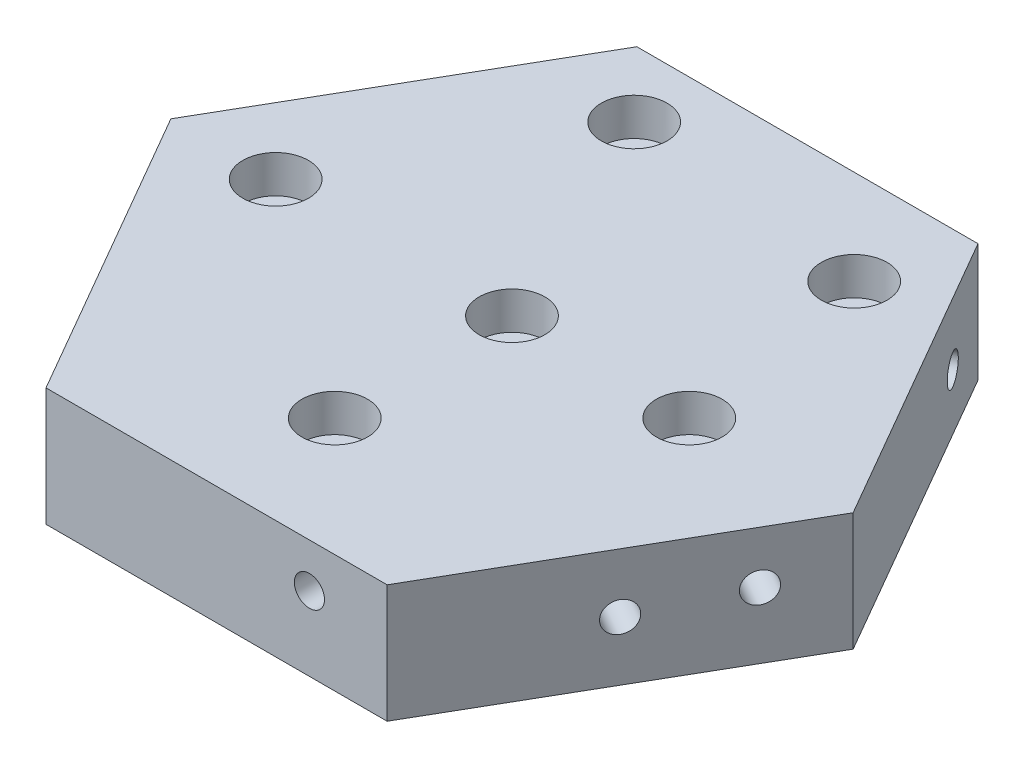
SolidWorks part; units mm, degrees
material "AISI 1020"
ref_plane "Front Plane" through (0, 0, 0) normal (0, 0, 1) x (1, 0, 0)
ref_plane "Top Plane" through (0, 0, 0) normal (0, 1, 0) x (1, 0, 0)
ref_plane "Right Plane" through (0, 0, 0) normal (1, 0, 0) x (0, 0, -1)
sketch "Sketch1" plane through (0, 0, 0) normal (0, 1, 0) x (1, 0, 0)
  line L0 (-43.3013, 25) -> (43.3013, -25) construction
  line L1 (28.8675, 50) -> (-28.8675, 50)
  line L2 (-28.8675, 50) -> (-57.735, 0)
  line L3 (-57.735, 0) -> (-28.8675, -50)
  line L4 (-28.8675, -50) -> (28.8675, -50)
  line L5 (28.8675, -50) -> (57.735, 0)
  line L6 (57.735, 0) -> (28.8675, 50)
  line L7 (0, -50) -> (0, 50) construction
  line L8 (-43.3013, -25) -> (43.3013, 25) construction
  circle A0 centre (0, 0) radius 50 construction
  dimension "D1" = 100
extrude "Boss-Extrude1" add sketch "Sketch1" along normal mid plane 20
sketch "Sketch2" plane through (0, 10, 0) normal (0, 1, 0) x (1, 0, 0)
  line L0 (0, 30) -> (0, -30) construction
  line L1 (-30, 0) -> (30, 0) construction
  circle A0 centre (0, 0) radius 30
  dimension "D1" = 60
hole_wizard "CBORE for 1/4 Socket Head Cap Screw1" positions "Sketch4" profile "Sketch3" counterbore size "1/4" standard "ANSI Inch" end condition through all
sketch "Sketch4" plane through (0, 10, 0) normal (0, 1, 0) x (1, 0, 0)
  line L0 (0, 0) -> (-40, 0) construction
  line L1 (-30, 0) -> (30, 0) construction
  point P2 (-18.0638, 38.7389)
  point P4 (23.901, 34.0116)
  point P6 (30, 0)
  point P9 (0, -30)
  point P12 (0, 0)
  point P18 (-40, 0)
  dimension "D1" = 40
sketch "Sketch3" plane through (-18.0638, 10, -38.7389) normal (1, 0, 0) x (0, 0, 1)
  line L0 (0, 0) -> (0, 20)
  line L1 (0, 20) -> (3.2639, 20)
  line L3 (3.2639, 20) -> (3.2639, 6.35)
  line L4 (3.2639, 6.35) -> (5.5562, 6.35)
  line L5 (5.5562, 6.35) -> (5.5562, 0)
  line L7 (5.5562, 0) -> (0, 0)
  line L11 (0, -6.35) -> (0, 107.95) construction
  dimension "Thru Hole Dia." = 6.5278
  dimension "Thru Hole Depth" = 20
  dimension "C'Bore Dia." = 11.1125
  dimension "C'Bore Depth" = 6.35
hole_wizard "1/4-20 Tapped Hole1" positions "3DSketch1" profile "Sketch5" tap size "1/4-20" standard "ANSI Inch"
sketch3d "3DSketch1"
  point P0 (15.7159, 2.5358, 50)
  point P2 (51.9652, 1.1471, 9.9936)
  point P4 (34.701, -0.4984, -39.8962)
  point P6 (-14.9517, 3.1221, -50)
  point P8 (-47.3852, 1.2793, -17.9265)
  point P10 (0, 0, -50)
  point P13 (43.3013, 0, -25)
  point P17 (43.3013, 0, 25)
sketch "Sketch5" plane through (15.7159, 2.5358, 50) normal (1, 0, 0) x (0, -1, 0)
  line L0 (0, 0) -> (0, 18.0438)
  line L1 (0, 18.0438) -> (2.5527, 16.51)
  line L2 (2.5527, 16.51) -> (2.5527, 0)
  line L5 (2.5527, 0) -> (0, 0)
  line L10 (0, 18.0438) -> (-2.5527, 16.51) construction
  line L11 (0, -6.35) -> (0, 107.95) construction
  dimension "Tap Drill Dia." = 5.1054
  dimension "Tap Drill Depth" = 16.51
  dimension "Drill Angle" = 118
cosmetic thread "Hole Thread1" parameters "D1"=12.7, "D2"=6.35
cosmetic thread "Hole Thread2" parameters "D1"=12.7, "D2"=6.35
cosmetic thread "Hole Thread3" parameters "D1"=12.7, "D2"=6.35
cosmetic thread "Hole Thread4" parameters "D1"=12.7, "D2"=6.35
cosmetic thread "Hole Thread5" parameters "D1"=12.7, "D2"=6.35
cosmetic thread "Hole Thread6" parameters "D1"=12.7, "D2"=6.35
cosmetic thread "Hole Thread7" parameters "D1"=12.7, "D2"=6.35
cosmetic thread "Hole Thread8" parameters "D1"=12.7, "D2"=6.35
